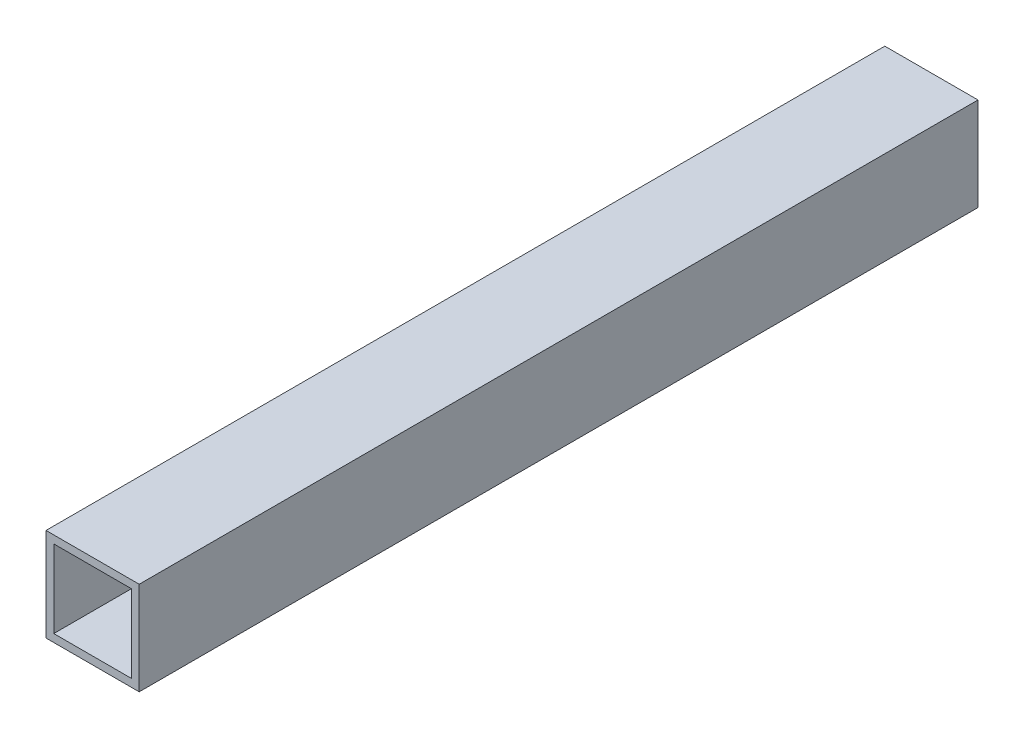
SolidWorks part; units mm, degrees
ref_plane "前视基准面" through (0, 0, 0) normal (0, 0, 1) x (1, 0, 0)
ref_plane "上视基准面" through (0, 0, 0) normal (0, 1, 0) x (1, 0, 0)
ref_plane "右视基准面" through (0, 0, 0) normal (1, 0, 0) x (0, 0, -1)
sketch "草图1" plane through (0, 0, 0) normal (0, 0, 1) x (1, 0, 0)
  line L0 (-12, 12) -> (12, 12)
  line L1 (-10, 10) -> (10, 10)
  line L2 (-10, 10) -> (-10, -10)
  line L3 (-10, -10) -> (10, -10)
  line L4 (10, 10) -> (10, -10)
  line L5 (-10, 10) -> (10, -10) construction
  line L6 (-10, -10) -> (10, 10) construction
  line L7 (12, 12) -> (12, -12)
  line L8 (-12, -12) -> (12, -12)
  line L9 (-12, 12) -> (-12, -12)
  point P0 (0, 0)
  dimension "D1" = 20
  dimension "D2" = 20
  dimension "D3" = 2
extrude "凸台-拉伸1" add sketch "草图1" along normal blind 216
